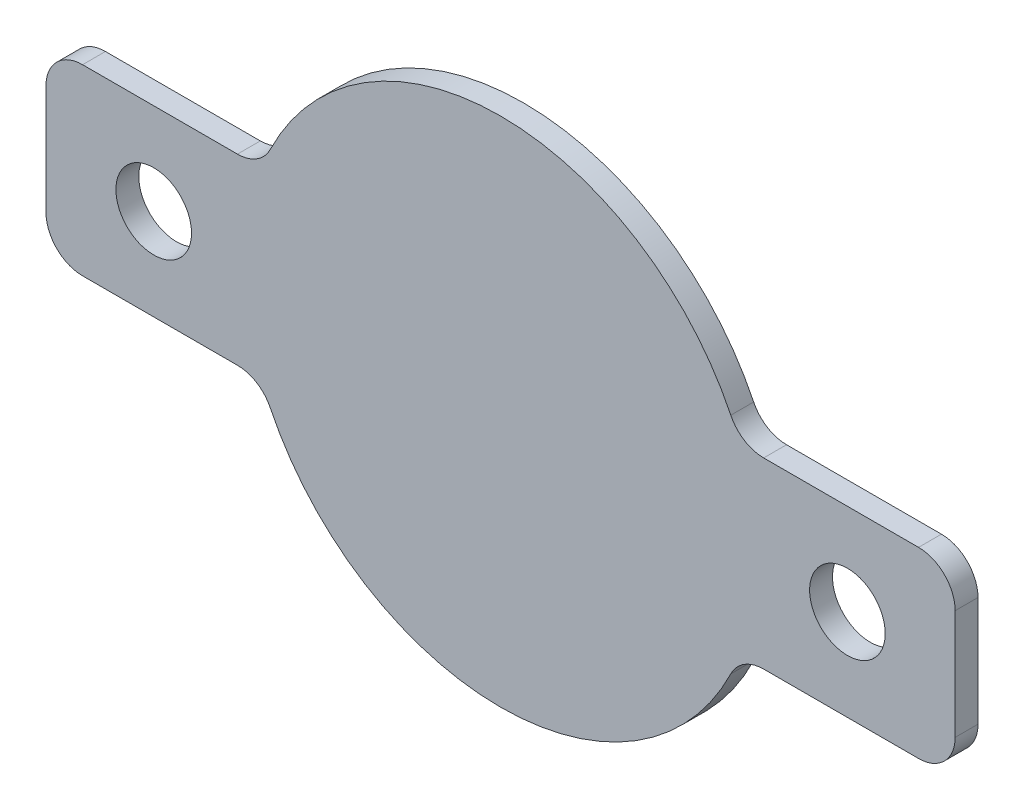
SolidWorks part; units mm, degrees
material "ABS"
ref_plane "X-Y Datum" through (0, 0, 0) normal (0, 0, 1) x (1, 0, 0)
ref_plane "X-Z Datum" through (0, 0, 0) normal (0, 1, 0) x (1, 0, 0)
ref_plane "Y-Z Datum" through (0, 0, 0) normal (1, 0, 0) x (0, 0, -1)
sketch "Sketch1" plane through (0, 0, 0) normal (0, 0, 1) x (-1, 0, 0)
  line L6 (-16.0929, 4.1604) -> (-31.0539, 4.1604)
  line L7 (-31.0539, 4.1604) -> (-31.0539, -8.5396)
  line L8 (-31.0539, -8.5396) -> (-16.0929, -8.5396)
  line L9 (17.122, 4.1604) -> (32.083, 4.1604)
  line L10 (32.083, 4.1604) -> (32.083, -8.5396)
  line L11 (32.083, -8.5396) -> (17.122, -8.5396)
  arc A2 (-16.0929, -8.5396) -> (17.122, -8.5396) centre (0.5145, -2.1896) ccw
  circle A3 centre (-23.5734, -2.1896) radius 2.625
  circle A4 centre (24.6025, -2.1896) radius 2.625
  arc A5 (17.122, 4.1604) -> (-16.0929, 4.1604) centre (0.5145, -2.1896) ccw
extrude "Boss-Extrude1" add sketch "Sketch1" along normal blind 1.5875
fillet "Fillet1" radius 2.54 8 edges at (16.0929, 8.5396, 0.7937) (-17.122, 8.5396, 0.7937) (-17.122, -4.1604, 0.7937) (16.0929, -4.1604, 0.7937) (-32.083, -4.1604, 0.7937) (-32.083, 8.5396, 0.7937) (31.0539, 8.5396, 0.7937) (31.0539, -4.1604, 0.7937)
